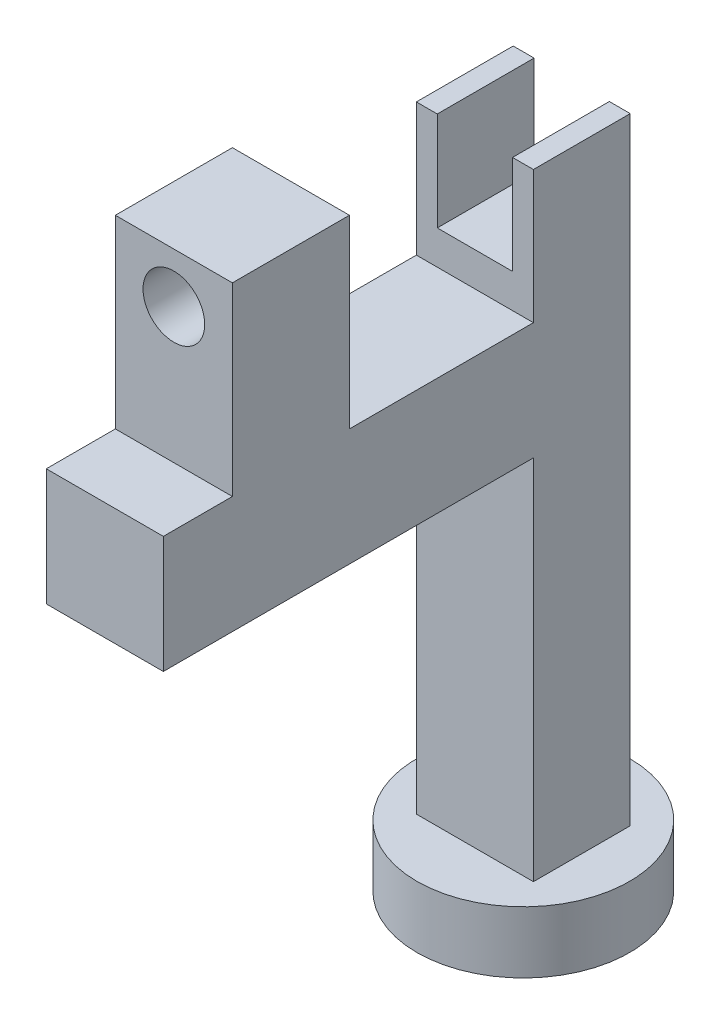
SolidWorks part; units mm, degrees
ref_plane "Front Plane" through (0, 0, 0) normal (0, 0, 1) x (1, 0, 0)
ref_plane "Top Plane" through (0, 0, 0) normal (0, 1, 0) x (1, 0, 0)
ref_plane "Right Plane" through (0, 0, 0) normal (1, 0, 0) x (0, 0, -1)
sketch "Sketch1" plane through (0, 0, 0) normal (0, 0, 1) x (1, 0, 0)
  line L0 (0, 0) -> (0, -100)
  line L1 (0, -100) -> (-18.9778, -100)
  line L2 (-18.9778, -100) -> (-18.9778, 0)
  line L3 (-18.9778, 0) -> (-15.5889, 0)
  line L4 (-15.5889, 0) -> (-15.5889, -16)
  line L5 (-15.5889, -16) -> (-3.3889, -16)
  line L6 (-3.3889, -16) -> (-3.3889, 0)
  line L7 (-3.3889, 0) -> (0, 0)
  dimension "D1" = 12.2
  dimension "D2" = 100
  dimension "D3" = 16
extrude "Boss-Extrude1" add sketch "Sketch1" along normal blind 15.7
sketch "Sketch2" plane through (0, -100, 0) normal (0, -1, 0) x (1, 0, 0)
  line L0 (0, 7.85) -> (-18.9778, 7.85) construction
  line L1 (0, 15.7) -> (0, 0) construction
  line L2 (-18.9778, 15.7) -> (-18.9778, 0) construction
  circle A0 centre (-9.4889, 7.85) radius 17.25
  dimension "D1" = 34.5
extrude "Boss-Extrude2" add sketch "Sketch2" along normal blind 10
sketch "Sketch4" plane through (0, -110, 0) normal (0, -1, 0) x (1, 0, 0)
  line L0 (-26.7389, 7.85) -> (7.7611, 7.85) construction
  circle A0 centre (-9.4889, 7.85) radius 17.25 construction
  circle A1 centre (-9.4889, 7.85) radius 0.8
  dimension "D1" = 1.6
extrude "Cut-Extrude1" cut sketch "Sketch4" against normal blind 2
sketch "Sketch5" plane through (0, 0, 15.7) normal (0, 0, 1) x (1, 0, 0)
  line L0 (-9.4889, -16) -> (-9.4889, -31) construction
  line L1 (-3.3889, -16) -> (-15.5889, -16) construction
  line L2 (-18.9778, 0) -> (-18.9778, -100) construction
  line L3 (0, -21.5111) -> (-18.9778, -21.5111)
  line L4 (0, -21.5111) -> (0, -40.4889)
  line L5 (0, -40.4889) -> (-18.9778, -40.4889)
  line L6 (-18.9778, -21.5111) -> (-18.9778, -40.4889)
  line L7 (0, -21.5111) -> (-18.9778, -40.4889) construction
  line L8 (0, -40.4889) -> (-18.9778, -21.5111) construction
  dimension "D1" = 15
extrude "Boss-Extrude3" add sketch "Sketch5" along normal blind 60
sketch "Sketch6" plane through (0, -21.5111, 0) normal (0, 1, 0) x (1, 0, 0)
  line L0 (-9.4889, -15.7) -> (-9.4889, -55.0159) construction
  line L1 (0, -15.7) -> (-18.9778, -15.7) construction
  line L2 (-18.9778, -75.7) -> (-18.9778, -15.7) construction
  line L3 (0, -64.5048) -> (-18.9778, -64.5048)
  line L4 (0, -64.5048) -> (0, -45.527)
  line L5 (0, -45.527) -> (-18.9778, -45.527)
  line L6 (-18.9778, -64.5048) -> (-18.9778, -45.527)
  line L7 (0, -64.5048) -> (-18.9778, -45.527) construction
  line L8 (0, -45.527) -> (-18.9778, -64.5048) construction
extrude "Boss-Extrude4" add sketch "Sketch6" along normal blind 30
sketch "Sketch7" plane through (0, 0, 45.527) normal (0, 0, -1) x (-1, 0, 0)
  line L0 (9.4889, -21.5111) -> (9.4889, 0.3989) construction
  line L1 (0, -21.5111) -> (18.9778, -21.5111) construction
  circle A0 centre (9.4889, 0.3989) radius 5
  dimension "D2" = 10
  dimension "D1" = 21.91
extrude "Cut-Extrude3" cut sketch "Sketch7" against normal up to next
